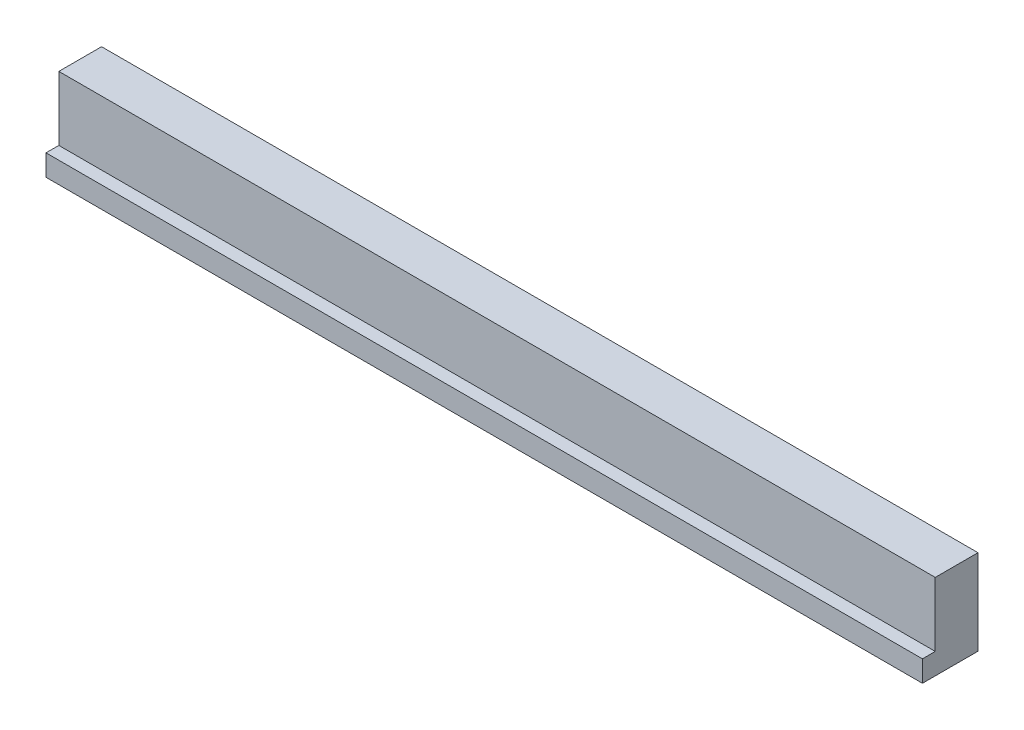
SolidWorks part; units mm, degrees
ref_plane "Front Plane" through (0, 0, 0) normal (0, 0, 1) x (1, 0, 0)
ref_plane "Top Plane" through (0, 0, 0) normal (0, 1, 0) x (1, 0, 0)
ref_plane "Right Plane" through (0, 0, 0) normal (1, 0, 0) x (0, 0, -1)
sketch "Sketch2" plane through (0, 0, 0) normal (1, 0, 0) x (0, 0, -1)
  line L0 (0, 0) -> (16.51, 0)
  line L1 (16.51, 0) -> (16.51, 25.3492)
  line L2 (16.51, 25.3492) -> (3.81, 25.3492)
  line L3 (3.81, 25.3492) -> (3.81, 6.2992)
  line L4 (3.81, 6.2992) -> (0, 6.2992)
  line L5 (0, 6.2992) -> (0, 0)
  dimension "D1" = 19.05
  dimension "D2" = 12.7
  dimension "D3" = 16.51
  dimension "D4" = 25.3492
extrude "Boss-Extrude1" add sketch "Sketch2" against normal blind 260.35
